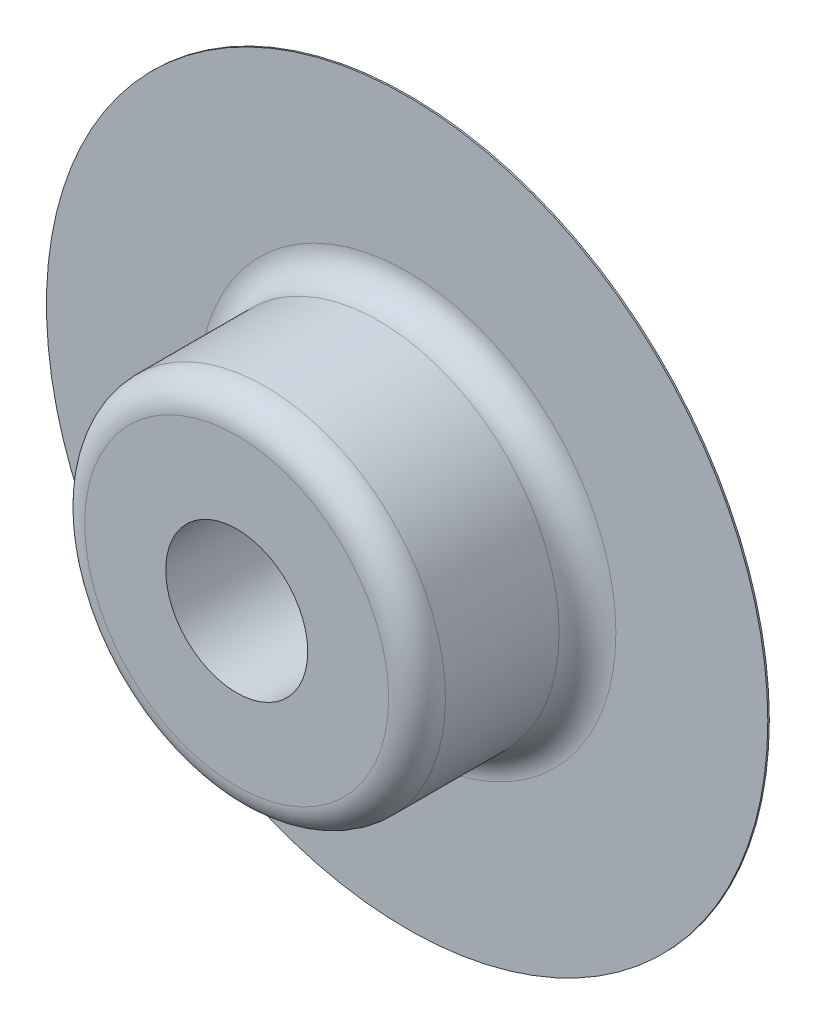
SolidWorks part; units mm, degrees
ref_plane "Płaszczyzna przednia" through (0, 0, 0) normal (0, 0, 1) x (1, 0, 0)
ref_plane "Płaszczyzna górna" through (0, 0, 0) normal (0, 1, 0) x (1, 0, 0)
ref_plane "Płaszczyzna prawa" through (0, 0, 0) normal (1, 0, 0) x (0, 0, -1)
sketch "Szkic1" plane through (0, 0, 0) normal (0, 0, 1) x (1, 0, 0)
  circle A0 centre (0, 0) radius 12.7
  dimension "D1" = 25.4
extrude "Dodanie-wyciągnięcie1" add sketch "Szkic1" along normal blind 0.054
sketch "Szkic2" plane through (0, 0, 0.054) normal (0, 0, 1) x (1, 0, 0)
  circle A0 centre (0, 0) radius 6.35
  dimension "D1" = 12.7
extrude "Dodanie-wyciągnięcie2" add sketch "Szkic2" along normal blind 6
sketch "Szkic3" plane through (0, 0, 6.054) normal (0, 0, 1) x (1, 0, 0)
  circle A0 centre (0, 0) radius 2.5
  dimension "D1" = 5
extrude "Wytnij-wyciągnięcie1" cut sketch "Szkic3" against normal through all both and the other way through all contours A0
fillet "Zaokrąglenie2" radius 1 2 edges at (6.35, 0, 0.054) (6.35, 0, 6.054)
